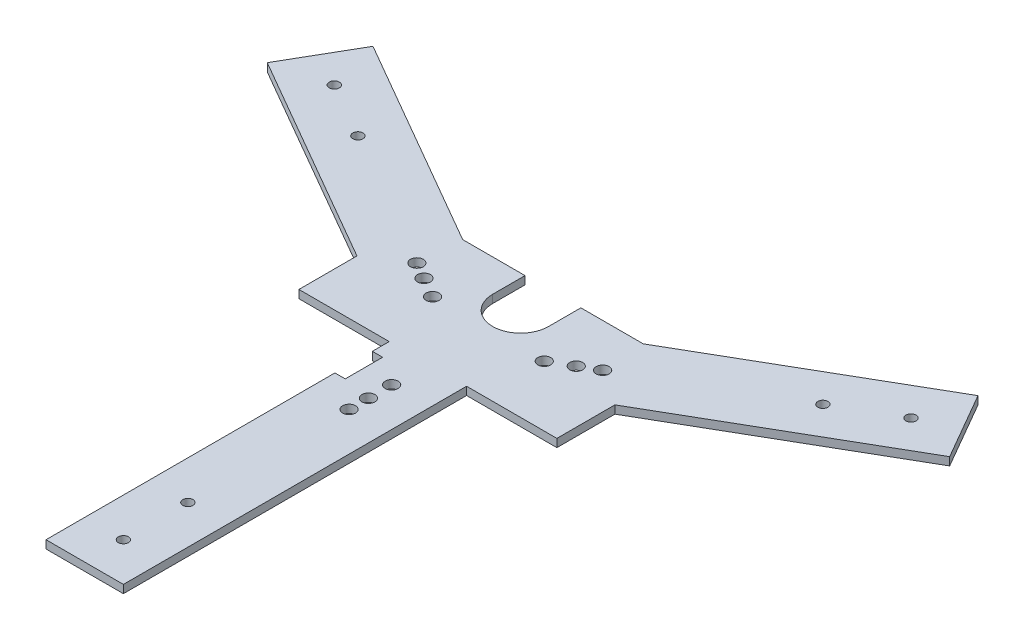
SolidWorks part; units mm, degrees
ref_plane "Front Plane" through (0, 0, 0) normal (0, 0, 1) x (1, 0, 0)
ref_plane "Top Plane" through (0, 0, 0) normal (0, 1, 0) x (1, 0, 0)
ref_plane "Right Plane" through (0, 0, 0) normal (1, 0, 0) x (0, 0, -1)
sketch "Sketch1" plane through (0, 0, 0) normal (0, 1, 0) x (1, 0, 0)
  line L0 (0, 11.43) -> (7.62, 24.6282)
  line L1 (0, 0) -> (50.8, 0)
  line L2 (0, 0) -> (0, 11.43)
  line L3 (0, 11.43) -> (50.8, 11.43)
  line L4 (50.8, 0) -> (50.8, 11.43)
  line L5 (50.8, 11.43) -> (43.18, 24.6282)
  line L6 (7.62, 24.6282) -> (43.18, 24.6282)
  line L7 (3.81, 18.0291) -> (44.3832, -5.3958) construction
  line L8 (17.78, 0) -> (33.02, 0)
  line L9 (17.78, 0) -> (17.78, -19.3279)
  line L10 (17.78, -19.3279) -> (33.02, -19.3279)
  line L11 (33.02, 0) -> (33.02, -19.3279)
  line L12 (46.99, 18.0291) -> (8.5613, -4.1577) construction
  line L13 (25.4, -19.3279) -> (25.4, 20.0669) construction
  line L14 (43.18, 24.6282) -> (50.8, 11.43)
  line L15 (19.9, 18.2641) -> (30.9, 18.2641)
  line L16 (19.9, 18.2641) -> (19.9, 24.6282)
  line L17 (19.9, 24.6282) -> (30.9, 24.6282)
  line L18 (30.9, 18.2641) -> (30.9, 24.6282)
  line L19 (17.78, -19.3279) -> (33.02, -19.3279)
  line L20 (17.78, -19.3279) -> (17.78, -67.5879)
  line L21 (17.78, -67.5879) -> (33.02, -67.5879)
  line L22 (33.02, -19.3279) -> (33.02, -67.5879)
  line L23 (43.18, 24.6282) -> (84.9744, 48.7582)
  line L24 (50.8, 11.43) -> (92.5944, 35.56)
  line L25 (84.9744, 48.7582) -> (92.5944, 35.56)
  line L26 (0, 11.43) -> (7.62, 24.6282)
  line L27 (0, 11.43) -> (-41.7944, 35.56)
  line L28 (7.62, 24.6282) -> (-34.1744, 48.7582)
  line L29 (-41.7944, 35.56) -> (-34.1744, 48.7582)
  circle A0 centre (43.6904, 16.1241) radius 1.27
  circle A1 centre (40.3909, 14.2191) radius 1.27
  circle A2 centre (36.3985, 11.9141) radius 1.27
  circle A3 centre (7.1096, 16.1241) radius 1.27
  circle A4 centre (10.4091, 14.2191) radius 1.27
  circle A5 centre (14.4015, 11.9141) radius 1.27
  circle A6 centre (25.4, -15.5179) radius 1.27
  circle A7 centre (25.4, -11.7079) radius 1.27
  circle A8 centre (25.4, -7.1359) radius 1.27
  circle A9 centre (25.4, 18.2641) radius 5.5
  point P23 (25.4, 5.5641)
  dimension "D11" = 3.81
  dimension "D12" = 3.81
  dimension "D13" = 2.54
  dimension "D14" = 2.54
  dimension "D15" = 2.54
  dimension "D16" = 12.7
  dimension "D17" = 3.81
  dimension "D18" = 3.81
  dimension "D19" = 2.54
  dimension "D20" = 2.54
  dimension "D21" = 2.54
  dimension "D22" = 3.81
  dimension "D23" = 3.81
  dimension "D24" = 12.7
  dimension "D25" = 2.54
  dimension "D26" = 2.54
  dimension "D27" = 2.54
  dimension "D28" = 12.7
  dimension "D29" = 11
  dimension "D1" = 50.8
  dimension "D2" = 11.43
  dimension "D3" = 30
  dimension "D4" = 15.24
  dimension "D5" = 30
  dimension "D6" = 15.24
  dimension "D7" = 15.24
  dimension "D8" = 24.892
  dimension "D9" = 17.78
  dimension "D10" = 12.7
  dimension "D30" = 48.26
  dimension "D31" = 48.26
  dimension "D32" = 48.26
extrude "Boss-Extrude2" add sketch "Sketch1" along normal blind 1.5875 contours A5 L3 L2 L1 L4 A2 | A5 L3 A2 L5 L6 L0 A4 A3 A1 A0 | L11 L1 L9 L10 A8 A7 A6 | L29 L27 L0 L28 | L22 L10 L20 L21 | L25 L23 L5 L24
sketch "Sketch6" plane through (0, 0, 0) normal (0, -1, 0) x (-1, 0, 0)
  line L0 (-17.78, 0) -> (-17.78, -67.5879) construction
  line L1 (-17.78, -10.6919) -> (-19.812, -10.6919)
  line L2 (-17.78, -10.6919) -> (-17.78, -3.3259)
  line L3 (-17.78, -3.3259) -> (-19.812, -3.3259)
  line L4 (-19.812, -10.6919) -> (-19.812, -3.3259)
  line L6 (0, 0) -> (-17.78, 0) construction
  dimension "D3" = 2.032
  dimension "D4" = 3.3259
  dimension "D5" = 10.6919
extrude "Cut-Extrude4" cut sketch "Sketch6" against normal blind 2.54
sketch "Sketch7" plane through (0, 0, 0) normal (0, -1, 0) x (-1, 0, 0)
  line L0 (-17.78, -67.5879) -> (-33.02, -67.5879) construction
  line L1 (-33.02, 0) -> (-33.02, -67.5879) construction
  line L2 (-43.18, 24.6282) -> (-84.9744, 48.7582) construction
  line L3 (-84.9744, 48.7582) -> (-92.5944, 35.56) construction
  line L4 (41.7944, 35.56) -> (34.1744, 48.7582) construction
  line L5 (-7.62, 24.6282) -> (34.1744, 48.7582) construction
  line L6 (0, 11.43) -> (41.7944, 35.56) construction
  circle A0 centre (-25.4, -59.9679) radius 1
  circle A1 centre (-25.4, -47.2679) radius 1
  circle A2 centre (-71.1867, 31.9991) radius 1
  circle A3 centre (-82.1853, 38.3491) radius 1
  circle A4 centre (31.3853, 38.3491) radius 1
  circle A5 centre (20.3867, 31.9991) radius 1
  dimension "D3" = 2
  dimension "D4" = 2
  dimension "D5" = 7.62
  dimension "D6" = 7.62
  dimension "D7" = 7.62
  dimension "D8" = 7.62
  dimension "D9" = 7.62
  dimension "D10" = 20.32
  dimension "D11" = 2
  dimension "D12" = 2
  dimension "D13" = 7.62
  dimension "D14" = 20.32
  dimension "D15" = 7.62
  dimension "D16" = 2
  dimension "D17" = 2
  dimension "D18" = 7.62
  dimension "D1" = 7.62
  dimension "D2" = 20.32
extrude "Cut-Extrude5" cut sketch "Sketch7" against normal blind 2.54
